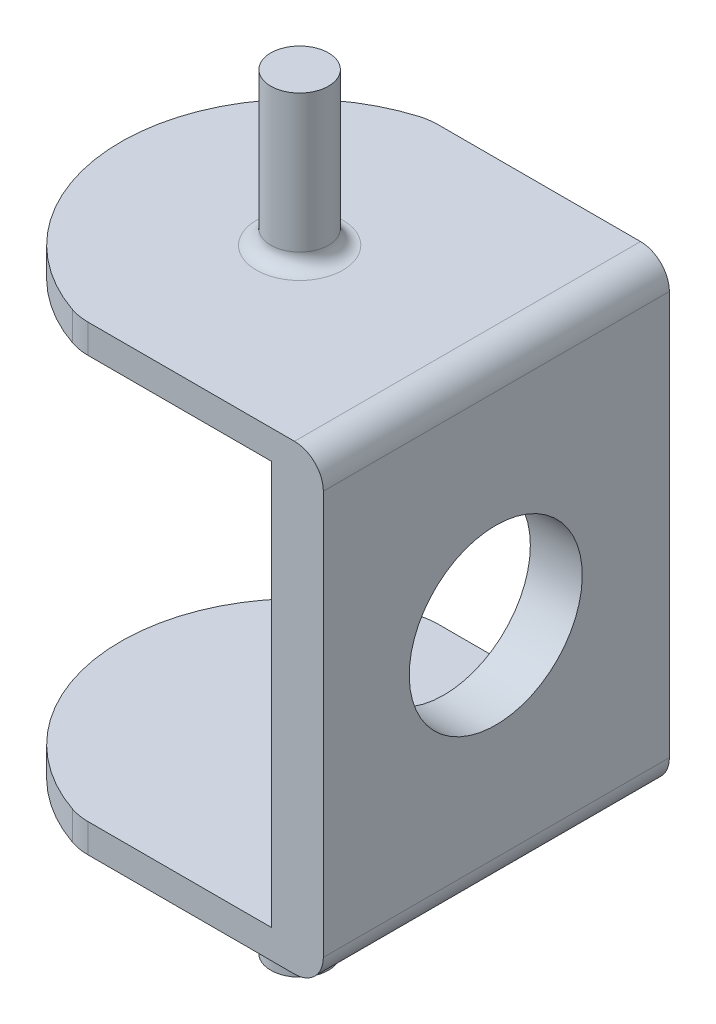
SolidWorks part; units mm, degrees
ref_plane "Front Plane" through (0, 0, 0) normal (0, 0, 1) x (1, 0, 0)
ref_plane "Top Plane" through (0, 0, 0) normal (0, 1, 0) x (1, 0, 0)
ref_plane "Right Plane" through (0, 0, 0) normal (1, 0, 0) x (0, 0, -1)
sketch "Sketch1" plane through (0, 0, 0) normal (0, 0, 1) x (1, 0, 0)
  line L0 (0, 132.6409) -> (0, -132.6409)
  line L1 (-137.1498, 0) -> (124.0031, 0) construction
  dimension "D1" = 265.2818
sweep "Sweep1" add path "Sketch1" circular profile diameter 20 parameters "D3"=20
sketch "Sketch8" plane through (0, 132.6409, 0) normal (0, 1, 0) x (1, 0, 0)
  circle A1 centre (0, 0) radius 10
  circle A2 centre (0, 0) radius 10
  dimension "D1" = 0
extrude "Boss-Extrude1" add sketch "Sketch8" along normal blind 0.25
ref_plane "Plane1" through (0, 0.125, 0) normal (0, 1, 0) x (1, 0, 0)
ref_plane "Plane2" through (0, 80.125, 0) normal (0, 1, 0) x (1, 0, 0)
sketch "Sketch9" plane through (0, 80.125, 0) normal (0, 1, 0) x (1, 0, 0)
  line L0 (0, 60.2135) -> (0, -59.7865) construction
  line L1 (60, 0.2135) -> (48.5761, 0.2135) construction
  line L2 (60, -59.7865) -> (-16.5831, -59.7865)
  line L3 (60, 60.2135) -> (-14.9585, 60.2135)
  line L4 (60, 60.2135) -> (60, -59.7865)
  arc A2 (-14.9585, 60.2135) -> (-16.5831, -59.7865) centre (0, 0) ccw
  point P5 (0, 0)
  point P13 (-16.5831, -59.7865)
  dimension "D1" = 60
  dimension "D3" = 60
extrude "Boss-Extrude2" add sketch "Sketch9" against normal blind 10
mirror "Mirror1" about plane through (0, 0.125, 0) normal (0, 1, 0) of "Boss-Extrude2"
sketch "Sketch14" plane through (0, 0, 59.7865) normal (0, 0, 1) x (1, 0, 0)
  line L0 (-16.5831, 70.125) -> (60, 70.125) construction
  line L1 (50, 70.125) -> (60, 70.125)
  line L2 (50, 70.125) -> (50, -69.875)
  line L3 (50, -69.875) -> (60, -69.875)
  line L5 (50, 70.125) -> (60, -69.875) construction
  line L6 (50, -69.875) -> (60, 70.125) construction
  line L7 (-16.5831, -69.875) -> (60, -69.875) construction
  line L9 (60, 80.125) -> (60, 70.125)
  line L10 (60, -69.875) -> (60, -79.875)
  line L11 (60, -79.875) -> (68, -79.875)
  line L12 (68, -79.875) -> (68, 80.125)
  line L13 (68, 80.125) -> (60, 80.125)
  point P0 (55, 0.125)
  dimension "D1" = 10
  dimension "D2" = 8
extrude "Boss-Extrude5" add sketch "Sketch14" against normal up to surface (120 mm away) up to face at (22.5207, -74.875, -60.2135)
sketch "Sketch15" plane through (50, 0, 0) normal (-1, 0, 0) x (0, 0, 1)
  line L4 (-60.2135, 70.125) -> (59.7865, 70.125)
  line L5 (59.7865, 70.125) -> (59.7865, -69.875)
  line L6 (59.7865, -69.875) -> (-60.2135, -69.875)
  line L7 (-60.2135, -69.875) -> (-60.2135, 70.125)
extrude "Cut-Extrude2" cut sketch "Sketch15" along normal blind 95
fillet "Fillet1" radius 5 2 edges at (10, -79.875, 0) (-10, 80.125, 0)
fillet "Fillet3" radius 20 4 edges at (-14.9585, 75.125, -60.2135) (-16.5831, -74.875, 59.7865) (-14.9585, -74.875, -60.2135) (-16.5831, 75.125, 59.7865)
fillet "Fillet4" radius 10 2 edges at (68, -79.875, -0.2135) (68, 80.125, -0.2135)
sketch "Sketch16" plane through (68, 0, 0) normal (1, 0, 0) x (0, 0, -1)
  circle A0 centre (0, 0) radius 30
extrude "Cut-Extrude3" cut sketch "Sketch16" against normal up to surface (18 mm away) up to face at (50, 0.125, -0.2135)
